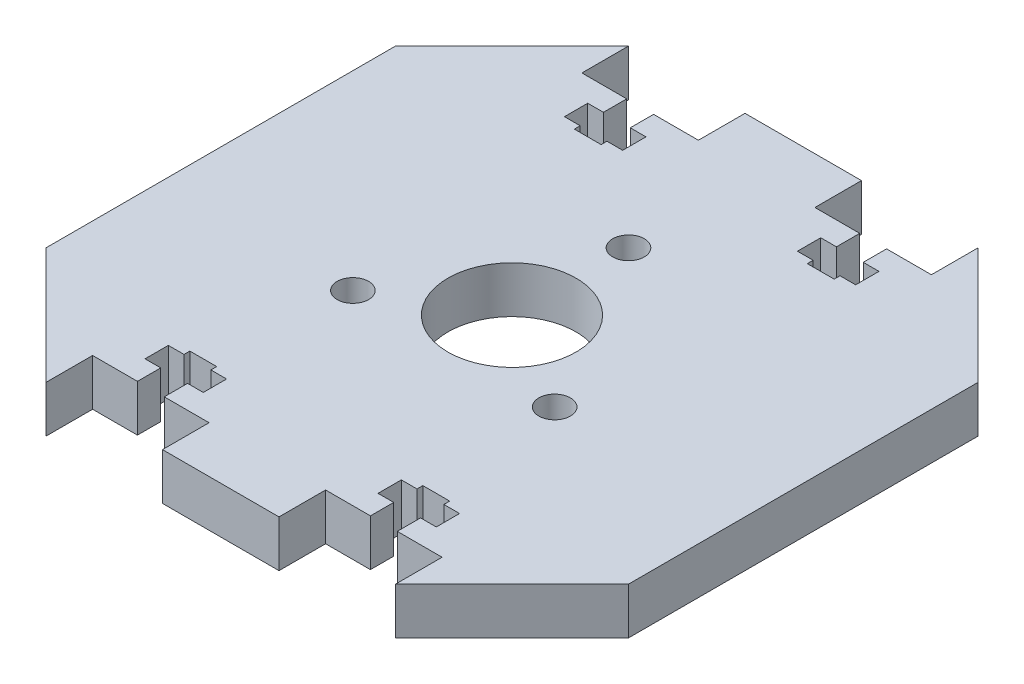
SolidWorks part; units mm, degrees
ref_plane "Front Plane" through (0, 0, 0) normal (0, 0, 1) x (1, 0, 0)
ref_plane "Top Plane" through (0, 0, 0) normal (0, 1, 0) x (1, 0, 0)
ref_plane "Right Plane" through (0, 0, 0) normal (1, 0, 0) x (0, 0, -1)
sketch "Sketch1" plane through (0, 0, 0) normal (0, 1, 0) x (1, 0, 0)
  line L0 (0, 15.875) -> (0, 8.7312) construction
  line L1 (-39.6875, 39.6875) -> (39.6875, 39.6875)
  line L2 (-39.6875, 39.6875) -> (-39.6875, -39.6875)
  line L3 (-39.6875, -39.6875) -> (39.6875, -39.6875)
  line L4 (39.6875, 39.6875) -> (39.6875, -39.6875)
  line L5 (-39.6875, 39.6875) -> (39.6875, -39.6875) construction
  line L6 (-39.6875, -39.6875) -> (39.6875, 39.6875) construction
  line L7 (-39.6875, 23.8125) -> (-23.8125, 39.6875)
  line L8 (-39.6875, -23.8125) -> (-23.8125, -39.6875)
  line L9 (0, 39.6875) -> (0, -39.6875) construction
  line L10 (39.6875, -23.8125) -> (23.8125, -39.6875)
  line L11 (39.6875, 23.8125) -> (23.8125, 39.6875)
  line L12 (-31.75, 39.6875) -> (-31.75, -39.6875) construction
  circle A0 centre (0, 0) radius 8.7312
  circle A1 centre (0, 15.875) radius 2.1526
  circle A2 centre (13.7482, -7.9375) radius 2.1527
  circle A3 centre (-13.7482, -7.9375) radius 2.1526
  circle A4 centre (-39.6875, 0) radius 23.8125
  point P16 (0, 0)
  dimension "D1" = 17.4625
  dimension "D2" = 4.3053
  dimension "D3" = 15.875
  dimension "D5" = 3
  dimension "D7" = 47.625
  dimension "D4" = 7.9375
  dimension "D6" = 7.1438
  dimension "D8" = 31.75
  dimension "D9" = 45
  dimension "D10" = 79.375
extrude "Boss-Extrude1" add sketch "Sketch1" along normal blind 6.35 contours A4 L8 L3 L10 L4 L11 L1 L7 A3 A2 A1 A0 | L2 A4 A3
sketch "Sketch2" plane through (0, 6.35, 0) normal (0, 1, 0) x (1, 0, 0)
  line L0 (-23.8125, -39.6875) -> (-7.9375, -39.6875)
  line L1 (-23.8125, -39.6875) -> (23.8125, -39.6875) construction
  line L2 (-23.8125, -39.6875) -> (-23.8125, -33.3375)
  line L3 (-23.8125, -33.3375) -> (-17.7038, -33.3375)
  line L4 (-7.9375, -33.3375) -> (-7.9375, -39.6875)
  line L5 (-7.9375, -39.6875) -> (7.9375, -39.6875)
  line L6 (19.8438, -30.1625) -> (19.8438, -26.9875)
  line L7 (19.8438, -26.9875) -> (17.7038, -26.9875)
  line L8 (17.7038, -26.9875) -> (17.7038, -26.1937)
  line L9 (17.7038, -26.1937) -> (14.0462, -26.1937)
  line L10 (-17.7038, -33.3375) -> (-17.7038, -30.1625)
  line L11 (-14.0462, -33.3375) -> (-14.0462, -30.1625)
  line L12 (-15.875, -33.3375) -> (-15.875, -26.9875) construction
  line L13 (-17.7038, -30.1625) -> (-19.8437, -30.1625)
  line L14 (-19.8437, -30.1625) -> (-19.8437, -26.9875)
  line L15 (-19.8437, -26.9875) -> (-17.7038, -26.9875)
  line L16 (-11.9062, -26.9875) -> (-11.9062, -30.1625)
  line L17 (-11.9062, -30.1625) -> (-14.0462, -30.1625)
  line L18 (-17.7038, -26.9875) -> (-17.7038, -26.1937)
  line L19 (-17.7038, -26.1937) -> (-14.0462, -26.1937)
  line L20 (-14.0462, -26.1937) -> (-14.0462, -26.9875)
  line L21 (-14.0462, -26.9875) -> (-11.9062, -26.9875)
  line L22 (-14.0462, -33.3375) -> (-7.9375, -33.3375)
  line L23 (0, -39.6875) -> (0, 39.6875) construction
  line L26 (-39.6875, 0) -> (39.6875, 0) construction
  line L27 (-39.6875, 23.8125) -> (-39.6875, -23.8125) construction
  line L28 (39.6875, 23.8125) -> (39.6875, -23.8125) construction
  line L29 (14.0462, -26.1937) -> (14.0462, -26.9875)
  line L30 (14.0462, -26.9875) -> (11.9063, -26.9875)
  line L31 (11.9063, -26.9875) -> (11.9063, -30.1625)
  line L32 (11.9063, -30.1625) -> (14.0462, -30.1625)
  line L33 (17.7038, -30.1625) -> (19.8438, -30.1625)
  line L34 (23.8125, -33.3375) -> (17.7038, -33.3375)
  line L35 (17.7038, -33.3375) -> (17.7038, -30.1625)
  line L36 (14.0462, -33.3375) -> (14.0462, -30.1625)
  line L37 (15.875, -33.3375) -> (15.875, -26.9875) construction
  line L38 (14.0462, -33.3375) -> (7.9375, -33.3375)
  line L39 (7.9375, -33.3375) -> (7.9375, -39.6875)
  line L40 (23.8125, -39.6875) -> (23.8125, -33.3375)
  line L41 (23.8125, -39.6875) -> (7.9375, -39.6875)
  line L42 (-23.8125, 39.6875) -> (-7.9375, 39.6875)
  line L43 (23.8125, 39.6875) -> (7.9375, 39.6875)
  line L44 (23.8125, 39.6875) -> (23.8125, 33.3375)
  line L45 (7.9375, 33.3375) -> (7.9375, 39.6875)
  line L46 (15.875, 33.3375) -> (15.875, 26.9875) construction
  line L47 (14.0462, 33.3375) -> (7.9375, 33.3375)
  line L48 (14.0462, 33.3375) -> (14.0462, 30.1625)
  line L49 (17.7038, 33.3375) -> (17.7038, 30.1625)
  line L50 (23.8125, 33.3375) -> (17.7038, 33.3375)
  line L51 (17.7038, 30.1625) -> (19.8438, 30.1625)
  line L52 (11.9063, 30.1625) -> (14.0462, 30.1625)
  line L53 (11.9063, 26.9875) -> (11.9063, 30.1625)
  line L54 (14.0462, 26.9875) -> (11.9063, 26.9875)
  line L55 (14.0462, 26.1937) -> (14.0462, 26.9875)
  line L56 (17.7038, 26.1937) -> (14.0462, 26.1937)
  line L57 (17.7038, 26.9875) -> (17.7038, 26.1937)
  line L58 (19.8438, 26.9875) -> (17.7038, 26.9875)
  line L59 (19.8438, 30.1625) -> (19.8438, 26.9875)
  line L60 (-15.875, 33.3375) -> (-15.875, 26.9875) construction
  line L61 (-14.0462, 33.3375) -> (-7.9375, 33.3375)
  line L62 (-14.0462, 26.9875) -> (-11.9062, 26.9875)
  line L63 (-14.0462, 26.1937) -> (-14.0462, 26.9875)
  line L64 (-17.7038, 26.1937) -> (-14.0462, 26.1937)
  line L65 (-17.7038, 26.9875) -> (-17.7038, 26.1937)
  line L66 (-11.9062, 30.1625) -> (-14.0462, 30.1625)
  line L67 (-11.9062, 26.9875) -> (-11.9062, 30.1625)
  line L68 (-19.8437, 26.9875) -> (-17.7038, 26.9875)
  line L69 (-19.8437, 30.1625) -> (-19.8437, 26.9875)
  line L70 (-17.7038, 30.1625) -> (-19.8437, 30.1625)
  line L71 (-14.0462, 33.3375) -> (-14.0462, 30.1625)
  line L72 (-17.7038, 33.3375) -> (-17.7038, 30.1625)
  line L73 (-7.9375, 33.3375) -> (-7.9375, 39.6875)
  line L74 (-23.8125, 33.3375) -> (-17.7038, 33.3375)
  line L75 (-23.8125, 39.6875) -> (-23.8125, 33.3375)
  line M28 (-23.8125, -39.6875) -> (23.8125, -39.6875)
  line M32 (23.8125, 39.6875) -> (-23.8125, 39.6875)
  dimension "D1" = 15.875
  dimension "D2" = 15.875
  dimension "D3" = 6.35
  dimension "D4" = 3.6576
  dimension "D5" = 3.175
  dimension "D6" = 3.175
  dimension "D7" = 7.9375
  dimension "D8" = 0.7937
  dimension "D9" = 3.6576
extrude "Cut-Extrude1" cut sketch "Sketch2" against normal through all contours L75 L74 L72 L70 L69 L68 L65 L64 L63 L62 L67 L66 L71 L61 L73 M32 | L59 L51 L49 L50 L44 L45 L47 L48 L52 L53 L54 L55 L56 L57 L58 M32 | L22 L11 L17 L16 L21 L20 L19 L18 L15 L14 L13 L10 L3 L2 L4 M28 | L40 L34 L35 L33 L6 L7 L8 L9 L29 L30 L31 L32 L36 L38 L39 M28
